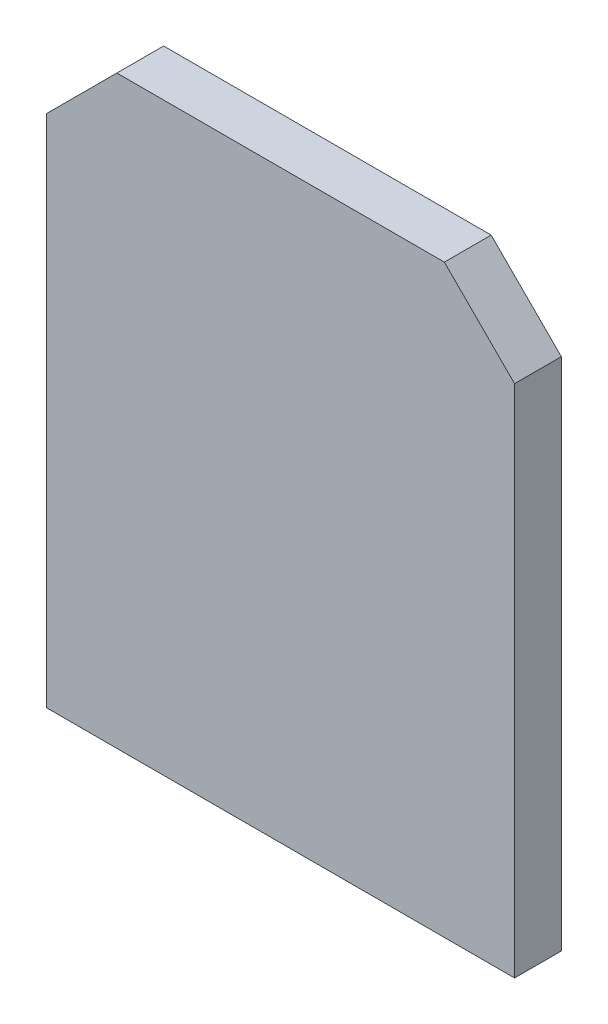
SolidWorks part; units mm, degrees
ref_plane "Front Plane" through (0, 0, 0) normal (0, 0, 1) x (1, 0, 0)
ref_plane "Top Plane" through (0, 0, 0) normal (0, 1, 0) x (1, 0, 0)
ref_plane "Right Plane" through (0, 0, 0) normal (1, 0, 0) x (0, 0, -1)
sketch "Sketch1" plane through (0, 0, 0) normal (0, 0, 1) x (1, 0, 0)
  line L0 (-25.4, 24.13) -> (-17.78, 31.75)
  line L1 (-25.4, -31.75) -> (25.4, -31.75)
  line L2 (-25.4, -31.75) -> (-25.4, 24.13)
  line L3 (-17.78, 31.75) -> (17.78, 31.75)
  line L4 (25.4, -31.75) -> (25.4, 24.13)
  line L5 (-25.4, -31.75) -> (25.4, 31.75) construction
  line L6 (-25.4, 31.75) -> (25.4, -31.75) construction
  line L7 (17.78, 31.75) -> (25.4, 24.13)
  point P0 (0, 0)
  dimension "D1" = 50.8
  dimension "D2" = 63.5
extrude "Boss-Extrude1" add sketch "Sketch1" along normal blind 5.08
